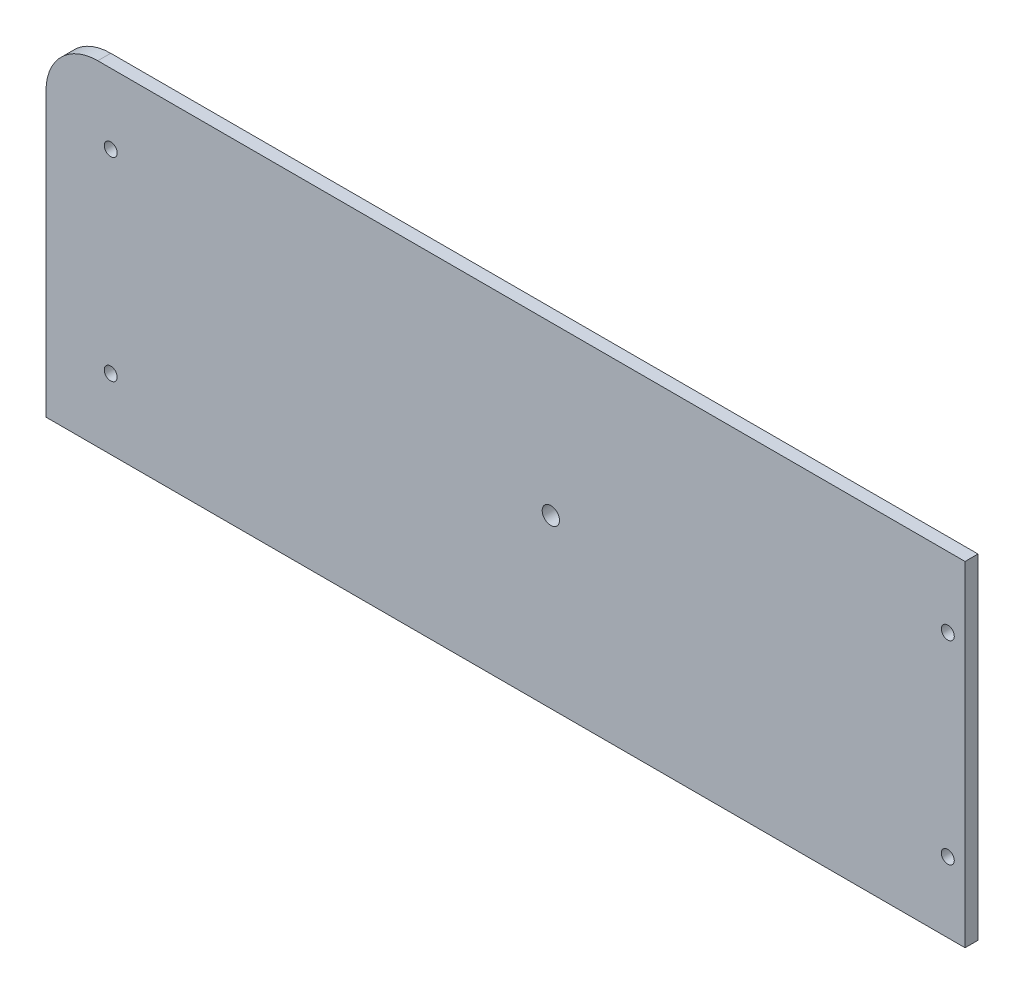
SolidWorks part; units mm, degrees
ref_plane "Front Plane" through (0, 0, 0) normal (0, 0, 1) x (1, 0, 0)
ref_plane "Top Plane" through (0, 0, 0) normal (0, 1, 0) x (1, 0, 0)
ref_plane "Right Plane" through (0, 0, 0) normal (1, 0, 0) x (0, 0, -1)
sketch "Sketch1" plane through (0, 0, 0) normal (0, 0, 1) x (1, 0, 0)
  line L1 (-106.5, -38.77) -> (106.5, -38.77)
  line L2 (-106.5, -38.77) -> (-106.5, 38.77)
  line L3 (-106.5, 38.77) -> (106.5, 38.77)
  line L4 (106.5, -38.77) -> (106.5, 38.77)
  line L5 (-106.5, -38.77) -> (106.5, 38.77) construction
  line L6 (-106.5, 38.77) -> (106.5, -38.77) construction
  point P0 (0, 0)
  dimension "D1" = 213
  dimension "D2" = 77.54
extrude "Boss-Extrude1" add sketch "Sketch1" along normal blind 3
fillet "Fillet2" radius 12 1 edges at (-106.5, 38.77, 1.5)
sketch "Sketch2" plane through (0, 0, 0) normal (0, 0, -1) x (-1, 0, 0)
  circle A0 centre (-10.5, 0) radius 2
  point P3 (-7.4022, 0)
  point P5 (0, 0)
  dimension "D1" = 4
  dimension "D2" = 10.5
extrude "Cut-Extrude1" cut sketch "Sketch2" against normal up to next
sketch "Sketch3" plane through (0, 0, 0) normal (0, 0, -1) x (-1, 0, 0)
  line L5 (-106.5, -38.77) -> (-106.5, 38.77) construction
  circle A0 centre (-102.5, 22.5) radius 1.5
  circle A1 centre (-102.5, -22.5) radius 1.5
  point P4 (0, 0)
  point P8 (0, 0)
  dimension "D1" = 3
  dimension "D2" = 3
  dimension "D3" = 45
  dimension "D4" = 22.5
  dimension "D5" = 4
extrude "Cut-Extrude2" cut sketch "Sketch3" against normal up to next
sketch "Sketch4" plane through (0, 0, 0) normal (0, 0, -1) x (-1, 0, 0)
  line L0 (-102.5, 22.5) -> (91.5, 22.5) construction
  line L1 (-102.5, -22.5) -> (91.5, -22.5) construction
  line L2 (106.5, 26.77) -> (106.5, -38.77) construction
  circle A0 centre (91.5, 22.5) radius 1.5
  circle A1 centre (91.5, -22.5) radius 1.5
  point P5 (0, 0)
  dimension "D1" = 3
  dimension "D2" = 3
  dimension "D3" = 15
extrude "Cut-Extrude3" cut sketch "Sketch4" against normal up to next
